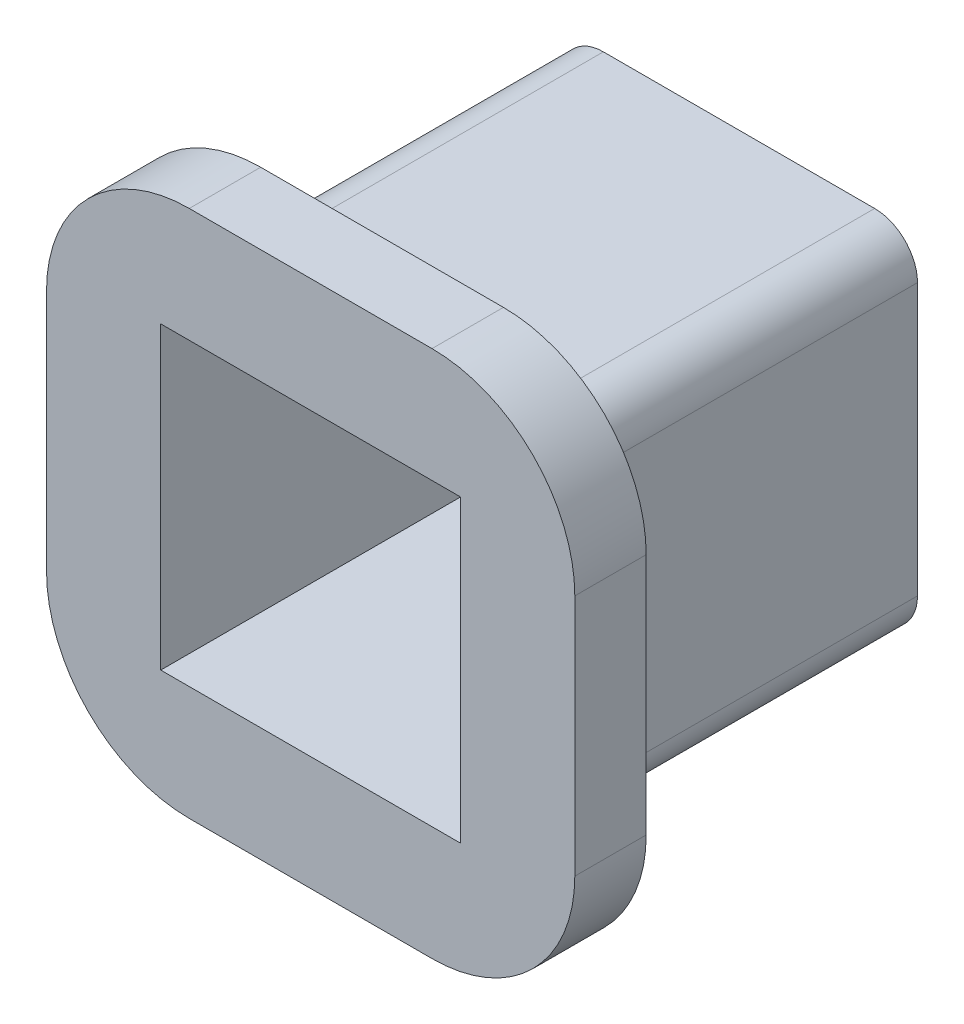
SolidWorks part; units mm, degrees
ref_plane "Plan de face" through (0, 0, 0) normal (0, 0, 1) x (1, 0, 0)
ref_plane "Plan de dessus" through (0, 0, 0) normal (0, 1, 0) x (1, 0, 0)
ref_plane "Plan de droite" through (0, 0, 0) normal (1, 0, 0) x (0, 0, -1)
sketch "Esquisse1" plane through (0, 0, 0) normal (0, 0, 1) x (1, 0, 0)
  line L0 (-10.5, 10.5) -> (-10.5, -10.5)
  line L1 (-12.5, 12.5) -> (12.5, 12.5)
  line L2 (-12.5, 12.5) -> (-12.5, -12.5)
  line L3 (-12.5, -12.5) -> (12.5, -12.5)
  line L4 (12.5, 12.5) -> (12.5, -12.5)
  line L5 (-12.5, 12.5) -> (12.5, -12.5) construction
  line L6 (-12.5, -12.5) -> (12.5, 12.5) construction
  line L7 (-10.5, -10.5) -> (10.5, -10.5)
  line L8 (10.5, 10.5) -> (10.5, -10.5)
  line L9 (-10.5, 10.5) -> (10.5, 10.5)
  point P0 (0, 0)
  dimension "D1" = 25
  dimension "D2" = 25
  dimension "D3" = 2
extrude "Boss.-Extru.1" add sketch "Esquisse1" along normal blind 30
sketch "Esquisse2" plane through (0, 0, 30) normal (0, 0, 1) x (1, 0, 0)
  line L0 (18.5, -18.5) -> (18.5, 18.5)
  line L1 (18.5, 18.5) -> (-18.5, 18.5)
  line L2 (-18.5, 18.5) -> (-18.5, -18.5)
  line L3 (-18.5, -18.5) -> (18.5, -18.5)
  line L4 (12.5, -12.5) -> (12.5, 12.5)
  line L5 (12.5, 12.5) -> (-12.5, 12.5)
  line L6 (-12.5, 12.5) -> (-12.5, -12.5)
  line L7 (-12.5, -12.5) -> (12.5, -12.5)
  line L8 (12.5, -12.5) -> (12.5, 12.5)
  line L9 (12.5, 12.5) -> (-12.5, 12.5)
  line L10 (-12.5, 12.5) -> (-12.5, -12.5)
  line L11 (-12.5, -12.5) -> (12.5, -12.5)
  dimension "D1" = 0
  dimension "D2" = 6
extrude "Boss.-Extru.2" add sketch "Esquisse2" against normal blind 5
fillet "Congé1" radius 10 4 edges at (18.5, -18.5, 27.5) (-18.5, -18.5, 27.5) (18.5, 18.5, 27.5) (-18.5, 18.5, 27.5)
fillet "Congé2" radius 3 4 edges at (-12.5, -12.5, 12.5) (12.5, -12.5, 12.5) (12.5, 12.5, 12.5) (-12.5, 12.5, 12.5)
